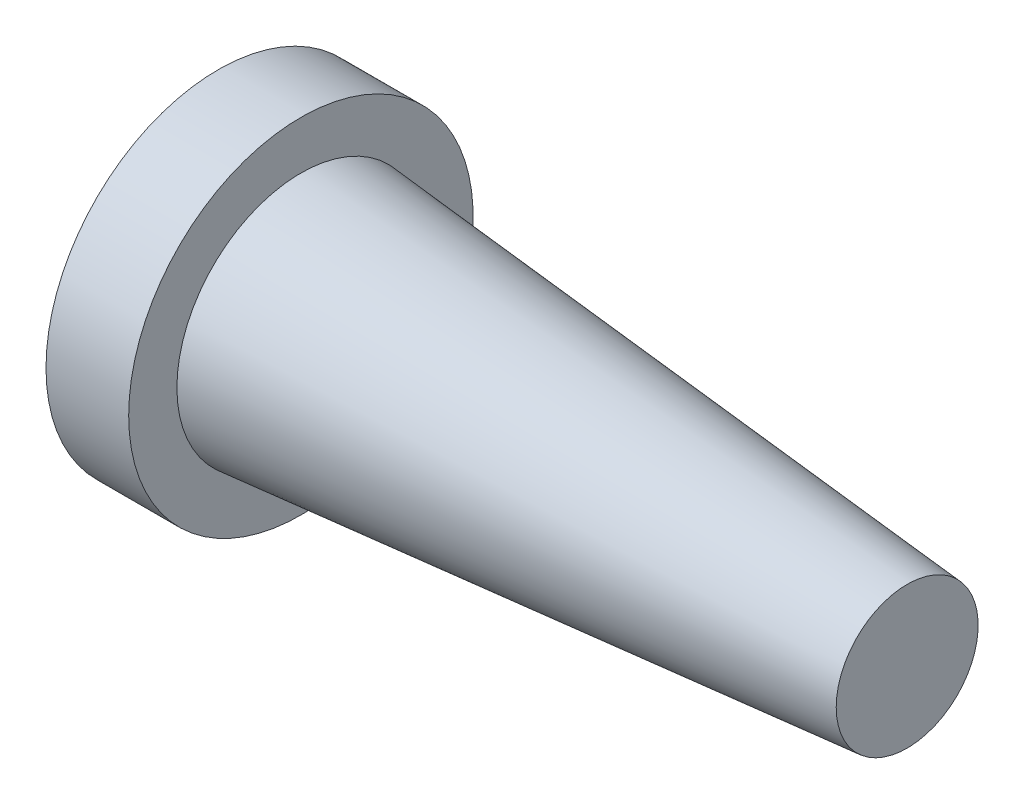
SolidWorks part; units mm, degrees
ref_plane "前视基准面" through (0, 0, 0) normal (0, 0, 1) x (1, 0, 0)
ref_plane "上视基准面" through (0, 0, 0) normal (0, 1, 0) x (1, 0, 0)
ref_plane "右视基准面" through (0, 0, 0) normal (1, 0, 0) x (0, 0, -1)
other "Configuration Table"
sketch "草图5" plane through (0, 0, 0) normal (0, 0, 1) x (1, 0, 0)
  line L0 (-110.0098, 0) -> (110.0098, 0) construction
  line L1 (-50, 0) -> (-50, 25)
  line L2 (-50, 25) -> (-38, 25)
  line L3 (-38, 25) -> (-38, 18)
  line L4 (-38, 18) -> (50, 10.301)
  line L5 (50, 10.301) -> (50, 0)
  line L6 (50, 0) -> (-50, 0)
  point P2 (-79.215, 0)
  point P4 (-78.6873, 0)
  point P10 (-50.36, 25)
  point P11 (43.0677, 10.301)
  dimension "D1" = 5
  dimension "D2" = 50
  dimension "D3" = 36
  dimension "D4" = 100
  dimension "D5" = 12
  dimension "D6" = 50
revolve "旋转1" add sketch "草图5" angle 360 about L0
sketch "草图9" plane through (-50, 0, 0) normal (-1, 0, 0) x (0, 0, 1)
  circle A0 centre (0, 0) radius 5
  dimension "D1" = 10
extrude "切除-拉伸2" cut sketch "草图9" against normal blind 30
hole_wizard "大小mm 暗销孔1" positions "草图10" profile "草图11" hole size "Ø4.0" standard "GB"
sketch "草图10" plane through (-20, 0, 0) normal (-1, 0, 0) x (0, 0, 1)
  point P0 (0, 0)
sketch "草图11" plane through (-20, 0, 0) normal (0, 1, 0) x (0, 0, 1)
  line L0 (0, 0) -> (0, 7.2017)
  line L1 (0, 7.2017) -> (2, 6)
  line L2 (2, 6) -> (2, 0)
  line L5 (2, 0) -> (0, 0)
  line L10 (0, 7.2017) -> (-2, 6) construction
  line L11 (0, -6.35) -> (0, 107.95) construction
  dimension "孔直径" = 4
  dimension "孔深度" = 6
  dimension "导头角度" = 118
ref_plane "基准面2" through (-26, 0, 0) normal (1, 0, 0) x (0, 0, -1)
sketch "草图13" plane through (-26, 0, 0) normal (1, 0, 0) x (0, 0, -1)
  circle A1 centre (0, 0) radius 17
  dimension "D1" = 34
curve "螺旋线/涡状线2"
